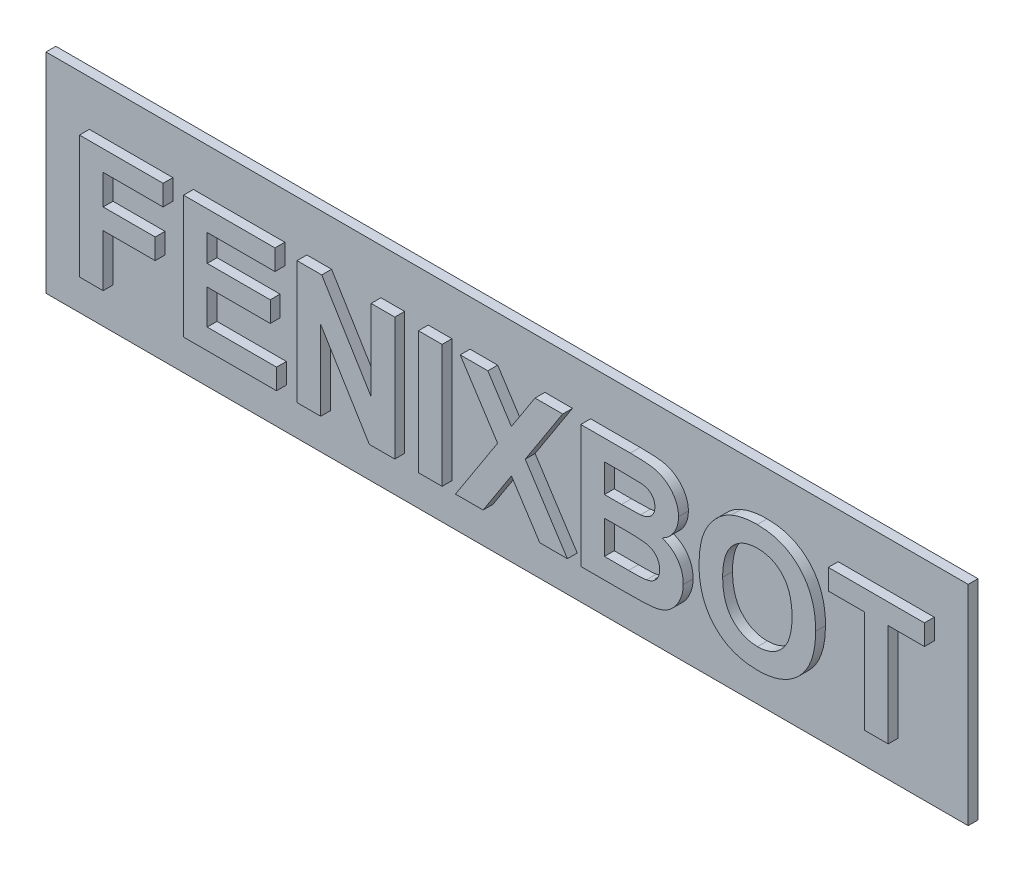
SolidWorks part; units mm, degrees
material "PET"
ref_plane "Alzado" through (0, 0, 0) normal (0, 0, 1) x (1, 0, 0)
ref_plane "Planta" through (0, 0, 0) normal (0, 1, 0) x (1, 0, 0)
ref_plane "Vista lateral" through (0, 0, 0) normal (1, 0, 0) x (0, 0, -1)
sketch "Croquis1" plane through (0, 0, 0) normal (0, 0, 1) x (1, 0, 0)
  line L0 (-35, 0) -> (35, 0) construction
  text T0 "FENIXBOT" font "Arial" height 10
  point P2 (0, 0)
  dimension "D1" = 70
extrude "Saliente-Extruir1" add sketch "Croquis1" along normal blind 0.8
sketch "Croquis2" plane through (0, 0, 0) normal (0, 0, 1) x (1, 0, 0)
  line L1 (-37.5, -3.3095) -> (37.5, -3.3095)
  line L2 (-37.5, -3.3095) -> (-37.5, 13.6905)
  line L3 (-37.5, 13.6905) -> (37.5, 13.6905)
  line L4 (37.5, -3.3095) -> (37.5, 13.6905)
  point P4 (0, -3.3095)
  dimension "D1" = 17
  dimension "D2" = 75
extrude "Saliente-Extruir2" add sketch "Croquis2" against normal blind 0.8
